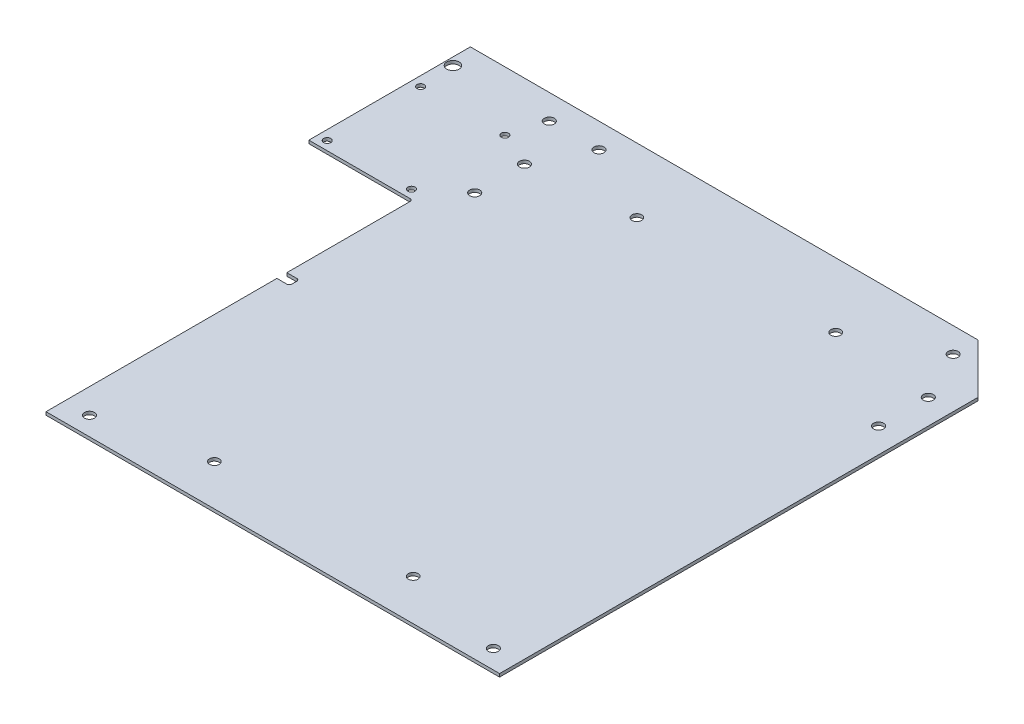
SolidWorks part; units mm, degrees
ref_plane "Front Plane" through (0, 0, 0) normal (0, 0, 1) x (1, 0, 0)
ref_plane "Top Plane" through (0, 0, 0) normal (0, 1, 0) x (1, 0, 0)
ref_plane "Right Plane" through (0, 0, 0) normal (1, 0, 0) x (0, 0, -1)
sketch "Sketch3" plane through (0, 0, 0) normal (0, 1, 0) x (1, 0, 0)
  line L1 (-177.119, 197.8912) -> (-149.179, 197.8912) construction
  line L2 (-96.1565, -3.6215) -> (-96.1565, 182.4335)
  line L5 (-149.179, 197.8912) -> (-149.179, 266.2535) construction
  line L6 (135.6185, -3.6215) -> (135.6185, 240.8535)
  line L7 (110.2185, 266.2535) -> (-70.7565, 266.2535)
  line L9 (-323.169, 266.2535) -> (337.231, 266.2535) construction
  line L11 (-70.7565, 266.2535) -> (-149.179, 266.2535)
  line L13 (135.6185, 240.8535) -> (110.2185, 266.2535)
  line L15 (-149.179, 266.2535) -> (-149.179, 183.7035)
  line L16 (-96.1565, -3.6215) -> (135.6185, -3.6215)
  line L17 (-149.179, 183.7035) -> (-97.4265, 183.7035)
  line L18 (-177.119, 253.5535) -> (-177.119, 183.7035) construction
  circle A0 centre (-83.4565, 202.7535) radius 6.35 construction
  arc A1 (-97.4265, 183.7035) -> (-96.1565, 182.4335) centre (-97.4265, 182.4335) cw
  point P3 (0, 0)
  dimension "D1" = 27.94
  dimension "D3" = 1.27
  dimension "D2" = 82.55
extrude "Boss-Extrude1" add sketch "Sketch3" along normal blind 1.5875
hole_wizard "#10 Clearance Hole1" positions "Sketch11" profile "Sketch12" hole size "#10" standard "ANSI Inch" end condition through all
sketch "Sketch11" plane through (0, 1.5875, 0) normal (0, 1, 0) x (1, 0, 0)
  point P0 (-83.4565, -25.8465)
  point P3 (-83.4565, 202.7535)
  point P6 (-83.4565, 228.1535)
  point P9 (-70.7565, 253.5535)
  point P12 (122.9185, 202.7535)
  point P15 (122.9185, 228.1535)
  point P18 (110.2185, 253.5535)
  point P21 (-83.4565, 5.9035)
  point P24 (122.9185, 5.9035)
  point P27 (-96.1565, 253.5535)
sketch "Sketch12" plane through (-83.4565, 1.5875, 25.8465) normal (1, 0, 0) x (0, 0, 1)
  line L0 (0, 0) -> (0, 1.5875)
  line L1 (0, 1.5875) -> (2.5527, 1.5875)
  line L2 (2.5527, 1.5875) -> (2.5527, 0)
  line L5 (2.5527, 0) -> (0, 0)
  line L11 (0, -6.35) -> (0, 107.95) construction
  dimension "Thru Hole Dia." = 5.1054
  dimension "Thru Hole Depth" = 1.5875
hole_wizard "1/4 (0.25) Diameter Hole1" positions "Sketch13" profile "Sketch14" hole size "1/4" standard "ANSI Inch" end condition through all
sketch "Sketch13" plane through (0, 0, 0) normal (0, -1, 0) x (-1, 0, 0)
  point P0 (145.369, 253.5535)
sketch "Sketch14" plane through (-145.369, 0, -253.5535) normal (1, 0, 0) x (0, 0, -1)
  line L0 (0, 0) -> (0, 1.5875)
  line L1 (0, 1.5875) -> (3.175, 1.5875)
  line L2 (3.175, 1.5875) -> (3.175, 0)
  line L5 (3.175, 0) -> (0, 0)
  line L11 (0, -6.35) -> (0, 107.95) construction
  dimension "Thru Hole Dia." = 6.35
  dimension "Thru Hole Depth" = 1.5875
hole_wizard "#6 Clearance Hole1" positions "Sketch15" profile "Sketch16" hole size "#6" standard "ANSI Inch" end condition through all
sketch "Sketch15" plane through (0, 1.5875, 0) normal (0, 1, 0) x (1, 0, 0)
  point P0 (-144.3052, 235.976)
  point P2 (-144.3052, 188.2264)
  point P4 (-101.2587, 188.2264)
  point P6 (-101.2587, 235.9784)
sketch "Sketch16" plane through (-144.3052, 1.5875, -235.976) normal (1, 0, 0) x (0, 0, 1)
  line L0 (0, 0) -> (0, 1.5875)
  line L1 (0, 1.5875) -> (1.8288, 1.5875)
  line L2 (1.8288, 1.5875) -> (1.8288, 0)
  line L5 (1.8288, 0) -> (0, 0)
  line L11 (0, -6.35) -> (0, 107.95) construction
  dimension "Thru Hole Dia." = 3.6576
  dimension "Thru Hole Depth" = 1.5875
sketch "Sketch17" plane through (0, 1.5875, 0) normal (0, 1, 0) x (1, 0, 0)
  line L0 (-96.1565, -3.6215) -> (-96.1565, 114.3615) construction
  line L1 (-96.1565, 182.4335) -> (-96.1565, -3.6215) construction
  line L2 (-96.1565, 114.3615) -> (-91.0765, 114.3615)
  line L3 (-89.8065, 115.6315) -> (-89.8065, 118.1715)
  line L4 (-91.0765, 119.4415) -> (-96.1565, 119.4415)
  line L5 (-96.1565, 119.4415) -> (-96.1565, 114.3615)
  arc A0 (-89.8065, 118.1715) -> (-91.0765, 119.4415) centre (-91.0765, 118.1715) ccw
  arc A1 (-91.0765, 114.3615) -> (-89.8065, 115.6315) centre (-91.0765, 115.6315) ccw
  point P10 (-89.8065, 119.4415)
  point P13 (-89.8065, 114.3615)
  dimension "D4" = 1.27
  dimension "D1" = 117.983
  dimension "D2" = 5.08
  dimension "D3" = 6.35
extrude "Cut-Extrude1" cut sketch "Sketch17" against normal through all
sketch "Sketch18" plane through (0, 1.5875, 0) normal (0, 1, 0) x (1, 0, 0)
  point P0 (-31.069, 17.3219)
  point P1 (70.531, 17.3219)
  point P3 (-31.069, 233.2219)
  point P5 (70.531, 233.2219)
hole_wizard "#10 Clearance Hole2" positions "Sketch21" profile "Sketch22" hole size "#10" standard "ANSI Inch" end condition through all
sketch "Sketch21" plane through (0, 1.5875, 0) normal (0, 1, 0) x (1, 0, 0)
  point P0 (-31.069, 233.2219)
  point P3 (70.531, 233.2219)
  point P6 (70.531, 17.3219)
  point P9 (-31.069, 17.3219)
sketch "Sketch22" plane through (-31.069, 1.5875, -233.2219) normal (1, 0, 0) x (0, 0, 1)
  line L0 (0, 0) -> (0, 1.5875)
  line L1 (0, 1.5875) -> (2.4892, 1.5875)
  line L2 (2.4892, 1.5875) -> (2.4892, 0)
  line L5 (2.4892, 0) -> (0, 0)
  line L11 (0, -6.35) -> (0, 107.95) construction
  dimension "Thru Hole Dia." = 4.9784
  dimension "Thru Hole Depth" = 1.5875
